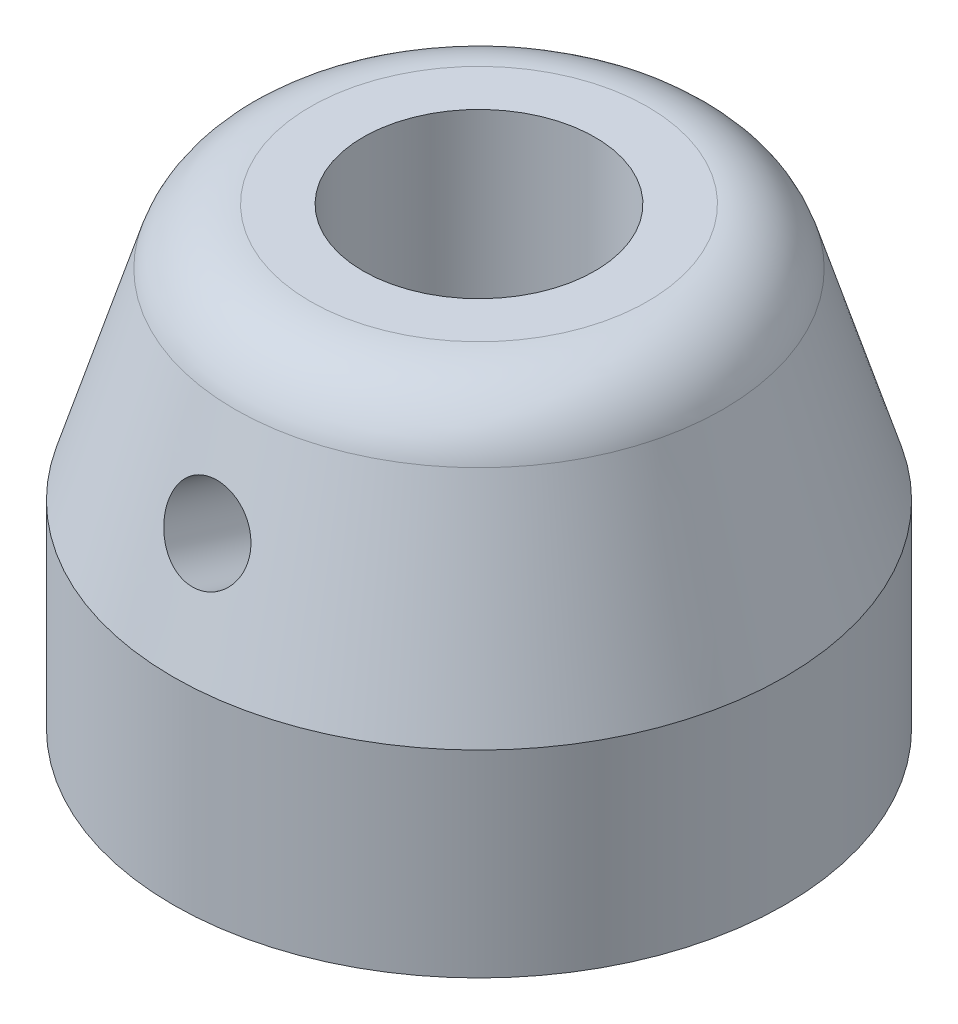
SolidWorks part; units mm, degrees
ref_plane "Front Plane" through (0, 0, 0) normal (0, 0, 1) x (1, 0, 0)
ref_plane "Top Plane" through (0, 0, 0) normal (0, 1, 0) x (1, 0, 0)
ref_plane "Right Plane" through (0, 0, 0) normal (1, 0, 0) x (0, 0, -1)
sketch "Sketch2" plane through (0, 0, 0) normal (0, 0, 1) x (1, 0, 0)
  line L0 (19.5959, 0) -> (31, 0)
  line L1 (31, 0) -> (31, 20)
  line L2 (31, 20) -> (23, 46)
  line L3 (23, 46) -> (0, 46)
  line L4 (0, 46) -> (0, 4)
  line L5 (0, 0) -> (0, -46) construction
  arc A1 (19.5959, 0) -> (0, 4) centre (0, -46) ccw
  dimension "D6" = 100
  dimension "D1" = 46
  dimension "D2" = 31
  dimension "D3" = 20
  dimension "D4" = 23
  dimension "D5" = 46
revolve "Revolve1" add sketch "Sketch2" angle 360 about L4
sketch "Sketch3" plane through (0, 46, 0) normal (0, 1, 0) x (1, 0, 0)
  circle A0 centre (0, 0) radius 12.5
  dimension "D1" = 25
fillet "Fillet1" radius 8 1 edges at (0, 46, 23)
sketch "Sketch22" plane through (0, 0, 0) normal (1, 0, 0) x (0, 0, -1)
  line L0 (0, 0) -> (-18.0959, 0)
  line L1 (-31, 0) -> (31, 0) construction
  line L2 (0, 0) -> (0, 2)
  line L3 (0, 2) -> (-12.5, 2)
  arc A0 (-12.5, 2) -> (-18.0959, 0) centre (1.5, -46) ccw
  dimension "D3" = 50
  dimension "D1" = 12.5
  dimension "D2" = 2
  dimension "D4" = 46
sketch "Sketch25" plane through (0, 0, 0) normal (1, 0, 0) x (0, 0, -1)
  line L0 (-24.5527, 40.3527) -> (-31, 20) construction
  line L1 (-24.7376, 40.3527) -> (24.7376, 40.3527) construction
  line L2 (-31, 20) -> (-31, 0) construction
  point P5 (-27.7763, 30.1763)
  dimension "D1" = 3.2237
hole_wizard "M10 Tapped Hole1" positions "3DSketch2" profile "Sketch27" tap size "M10" standard "ISO"
sketch3d "3DSketch2"
  point P0 (-0.142, 30.8492, 27.6614)
  dimension "D1" = 10
  dimension "D2" = 11.3522
cosmetic thread "Hole Thread1" parameters "D1"=10, "D2"=10
sketch "Sketch27" plane through (-0.142, 30.8492, 27.6614) normal (0.6915, 0.6915, -0.2092) x (0.7224, -0.6598, 0.2067)
  line L0 (0, 0) -> (0, 12.5537)
  line L1 (0, 12.5537) -> (4.25, 10)
  line L2 (4.25, 10) -> (4.25, 0)
  line L5 (4.25, 0) -> (0, 0)
  line L10 (0, 12.5537) -> (-4.25, 10) construction
  line L11 (0, -6.35) -> (0, 107.95) construction
  dimension "Tap Drill Dia." = 8.5
  dimension "Tap Drill Depth" = 10
  dimension "Drill Angle" = 118
hole_wizard "M25x1.5 Tapped Hole1" positions "3DSketch3" profile "Sketch28" tap size "M25x1.5" standard "DIN" end condition through all
sketch3d "3DSketch3"
  point P0 (0, 46, 0)
sketch "Sketch28" plane through (0, 46, 0) normal (1, 0, 0) x (0, 0, 1)
  line L0 (0, 0) -> (0, 46)
  line L1 (0, 46) -> (11.75, 46)
  line L2 (11.75, 46) -> (11.75, 0)
  line L5 (11.75, 0) -> (0, 0)
  line L11 (0, -6.35) -> (0, 107.95) construction
  dimension "Thru Tap Drill Dia." = 23.5
  dimension "Thru Tap Drill Depth" = 46
cosmetic thread "Hole Thread2" parameters "D2"=25
